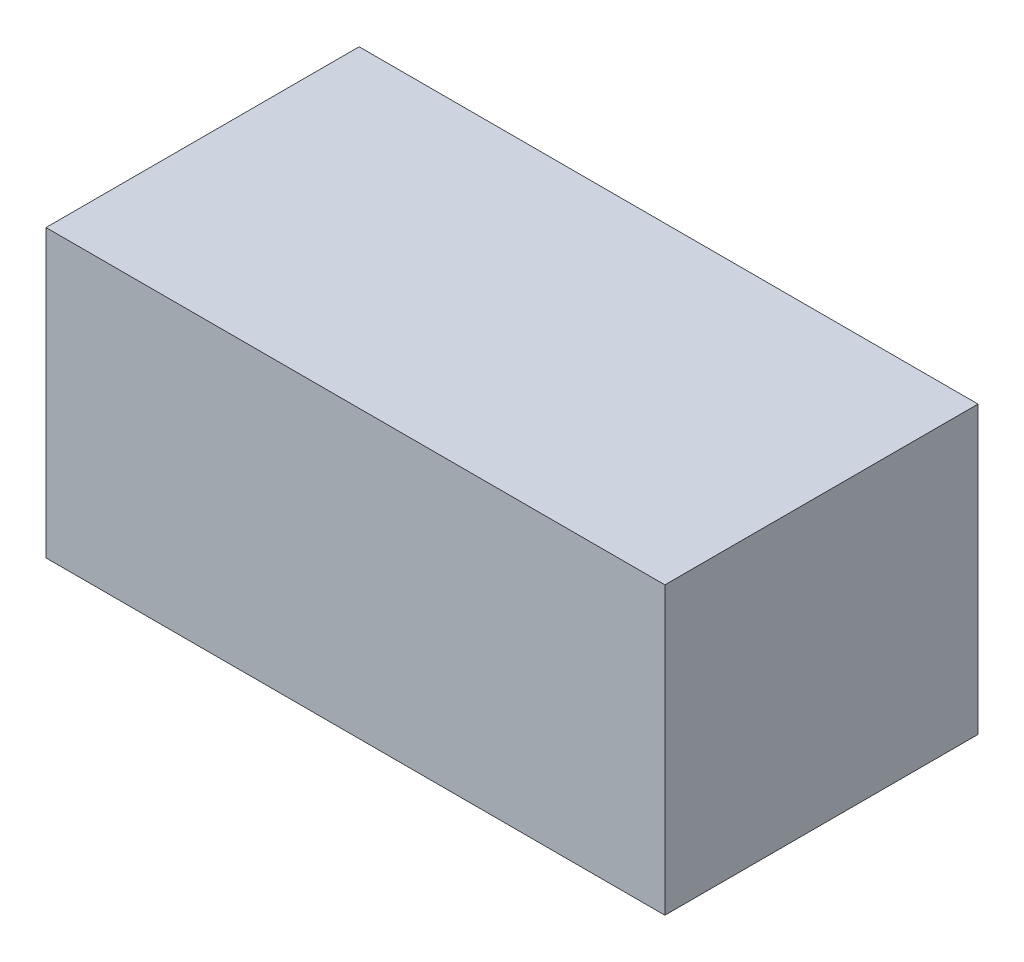
SolidWorks part; units mm, degrees
ref_plane "Front Plane" through (0, 0, 0) normal (0, 0, 1) x (1, 0, 0)
ref_plane "Top Plane" through (0, 0, 0) normal (0, 1, 0) x (1, 0, 0)
ref_plane "Right Plane" through (0, 0, 0) normal (1, 0, 0) x (0, 0, -1)
sketch "Sketch1" plane through (0, 0, 0) normal (0, 0, 1) x (1, 0, 0)
  line L1 (48.0707, -22.225) -> (-48.0707, -22.225)
  line L2 (48.0707, -22.225) -> (48.0707, 22.225)
  line L3 (48.0707, 22.225) -> (-48.0707, 22.225)
  line L4 (-48.0707, -22.225) -> (-48.0707, 22.225)
  line L5 (48.0707, -22.225) -> (-48.0707, 22.225) construction
  line L6 (48.0707, 22.225) -> (-48.0707, -22.225) construction
  point P0 (0, 0)
  dimension "D1" = 96.1414
  dimension "D2" = 44.45
extrude "Boss-Extrude1" add sketch "Sketch1" along normal blind 48.6422
